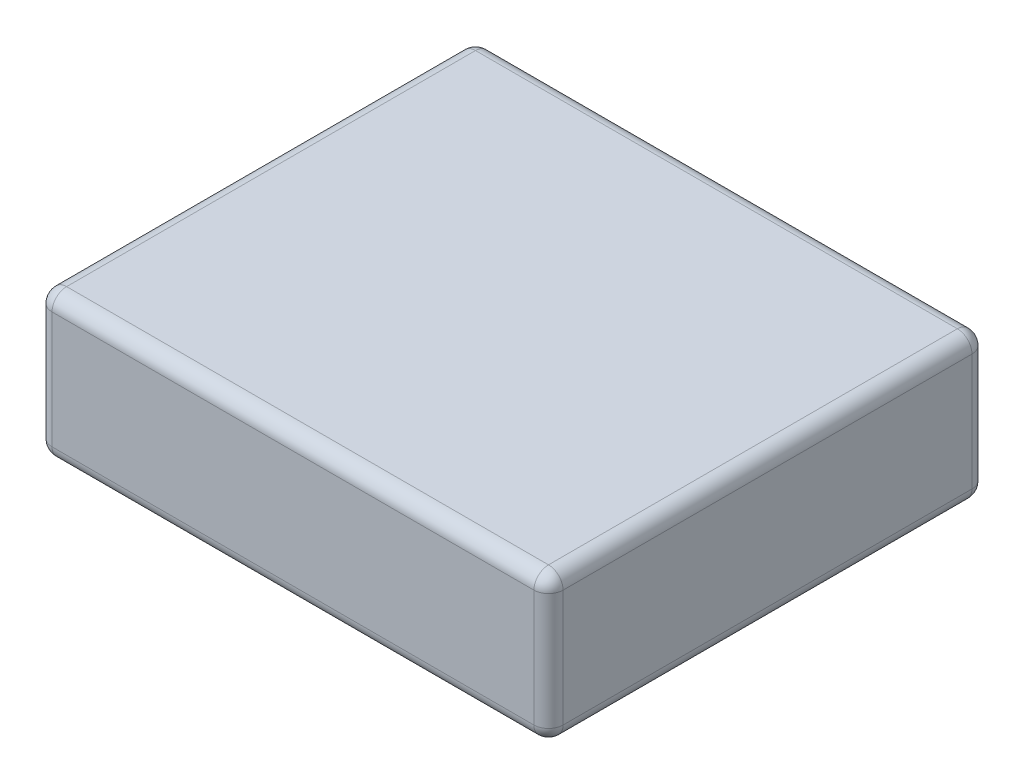
SolidWorks part; units mm, degrees
ref_plane "Front Plane" through (0, 0, 0) normal (0, 0, 1) x (1, 0, 0)
ref_plane "Top Plane" through (0, 0, 0) normal (0, 1, 0) x (1, 0, 0)
ref_plane "Right Plane" through (0, 0, 0) normal (1, 0, 0) x (0, 0, -1)
sketch "Sketch1" plane through (0, 0, 0) normal (0, 0, 1) x (1, 0, 0)
  line L1 (-33.3557, 4.849) -> (36.6443, 4.849)
  line L2 (-33.3557, 4.849) -> (-33.3557, -15.151)
  line L3 (-33.3557, -15.151) -> (36.6443, -15.151)
  line L4 (36.6443, 4.849) -> (36.6443, -15.151)
  line L5 (-33.3557, 4.849) -> (36.6443, -15.151) construction
  line L6 (-33.3557, -15.151) -> (36.6443, 4.849) construction
  point P0 (1.6443, -5.151)
  dimension "D1" = 70
  dimension "D2" = 20
extrude "Boss-Extrude1" add sketch "Sketch1" along normal blind 60
fillet "Fillet1" radius 2 12 edges at (-33.3557, 4.849, 30) (-33.3557, -15.151, 30) (1.6443, 4.849, 0) (-33.3557, -5.151, 0) (1.6443, -15.151, 0) (36.6443, -15.151, 30) (36.6443, 4.849, 30) (36.6443, -5.151, 0) (1.6443, -15.151, 60) (-33.3557, -5.151, 60) (1.6443, 4.849, 60) (36.6443, -5.151, 60)
